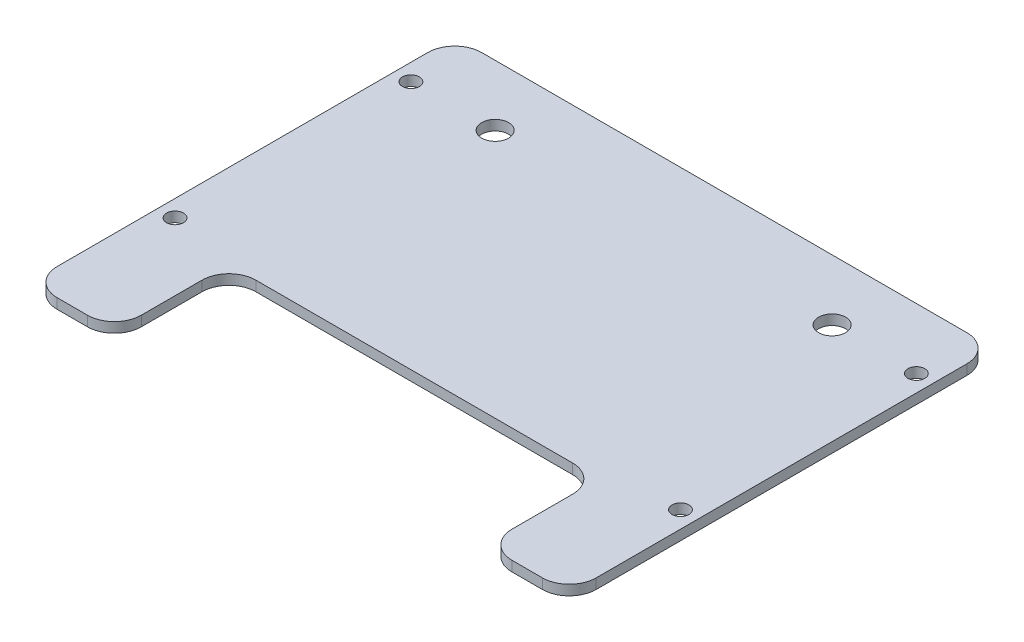
SolidWorks part; units mm, degrees
material "3.0205 (EN-AW 1200)"
ref_plane "Plan de face" through (0, 0, 0) normal (0, 0, 1) x (1, 0, 0)
ref_plane "Plan de dessus" through (0, 0, 0) normal (0, 1, 0) x (1, 0, 0)
ref_plane "Plan de droite" through (0, 0, 0) normal (1, 0, 0) x (0, 0, -1)
sketch "Esquisse1" plane through (0, 0, 0) normal (0, 1, 0) x (1, 0, 0)
  line L1 (-40, -63) -> (40, -63)
  line L2 (-40, -63) -> (-40, 0)
  line L3 (-40, 0) -> (40, 0)
  line L4 (40, -63) -> (40, 0)
  dimension "D1" = 80
  dimension "D2" = 63
extrude "Boss.-Extru.1" add sketch "Esquisse1" along normal blind 1.5
sketch "Esquisse2" plane through (0, 1.5, 0) normal (0, 1, 0) x (1, 0, 0)
  line L0 (-40, -63) -> (40, -63) construction
  line L1 (-27.5, -63) -> (27.5, -63)
  line L2 (-27.5, -63) -> (-27.5, -46)
  line L3 (-27.5, -46) -> (27.5, -46)
  line L4 (27.5, -63) -> (27.5, -46)
  line L5 (0, -46) -> (0, 0) construction
  line L6 (40, 0) -> (-40, 0) construction
  line L7 (-40, 0) -> (-40, -63) construction
  circle A0 centre (-37.5, -44) radius 1.25
  circle A1 centre (-37.5, -9) radius 1.25
  circle A2 centre (-25, -9) radius 2
  circle A3 centre (25, -9) radius 2
  circle A4 centre (37.5, -9) radius 1.25
  circle A5 centre (37.5, -44) radius 1.25
  point P4 (0, -63)
  dimension "D1" = 2.5
  dimension "D2" = 4
  dimension "D3" = 50
  dimension "D4" = 35
  dimension "D5" = 9
  dimension "D6" = 9
  dimension "D7" = 2.5
  dimension "D9" = 37
  dimension "D8" = 12.5
extrude "Enlèv. mat.-Extru.1" cut sketch "Esquisse2" against normal through all
fillet "Congé1" radius 4 8 edges at (-40, 0.75, 0) (27.5, 0.75, 46) (40, 0.75, 0) (40, 0.75, 63) (27.5, 0.75, 63) (-27.5, 0.75, 46) (-27.5, 0.75, 63) (-40, 0.75, 63)
